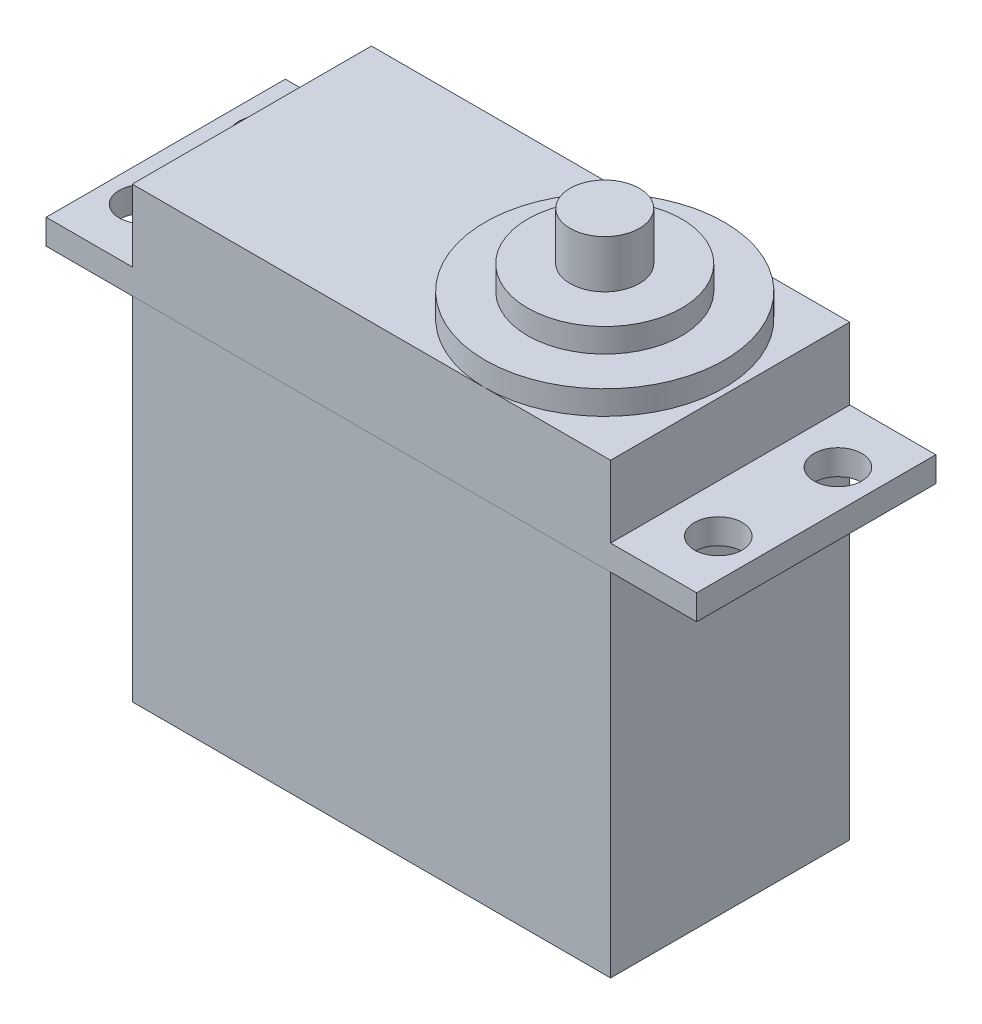
SolidWorks part; units mm, degrees
ref_plane "Alzado" through (0, 0, 0) normal (0, 0, 1) x (1, 0, 0)
ref_plane "Planta" through (0, 0, 0) normal (0, 1, 0) x (1, 0, 0)
ref_plane "Vista lateral" through (0, 0, 0) normal (1, 0, 0) x (0, 0, -1)
sketch "Croquis1" plane through (0, 0, 0) normal (0, 1, 0) x (1, 0, 0)
  line L0 (0, 0) -> (40, 0)
  line L1 (40, 0) -> (40, -20)
  line L2 (0, 0) -> (0, -20)
  line L3 (0, -20) -> (40, -20)
extrude "Saliente-Extruir1" add sketch "Croquis1" along normal blind 29.4
sketch "Croquis2" plane through (0, 29.4, 0) normal (0, 1, 0) x (1, 0, 0)
  line L0 (20, 0) -> (-7.2, 0)
  line L1 (40, 0) -> (0, 0) construction
  line L2 (20, 0) -> (47.2, 0)
  line L3 (-7.2, 0) -> (-7.2, -20.0033)
  line L4 (-7.2, -20.0033) -> (47.2, -20.0033)
  line L5 (47.2, -20.0033) -> (47.2, 0)
extrude "Saliente-Extruir2" add sketch "Croquis2" along normal blind 2.1
sketch "Croquis3" plane through (0, 31.5, 0) normal (0, 1, 0) x (1, 0, 0)
  circle A0 centre (-4.0958, -5.0008) radius 2
  circle A1 centre (-4.0958, -15.0025) radius 2
  circle A2 centre (44.0105, -5.0008) radius 2
  circle A3 centre (44.0105, -15.0025) radius 2
extrude "Cortar-Extruir1" cut sketch "Croquis3" against normal blind 2.1
sketch "Croquis4" plane through (0, 31.5, 0) normal (0, 1, 0) x (1, 0, 0)
  line L2 (0, 0) -> (0, -20.0033)
  line L3 (-7.2, -20.0033) -> (47.2, -20.0033) construction
  line L4 (0, -20.0033) -> (40.0016, -20.0033)
  line L5 (40.0016, -20.0033) -> (40, 0)
  line L6 (40, 0) -> (0, 0)
extrude "Saliente-Extruir3" add sketch "Croquis4" along normal blind 6
sketch "Croquis5" plane through (0, 37.5, 0) normal (0, 1, 0) x (1, 0, 0)
  line L0 (40.0008, -10.0017) -> (29.5104, -10.0017)
  line L1 (40.0016, -20.0033) -> (40, 0) construction
  circle A0 centre (29.5104, -10.0017) radius 10.0017
extrude "Saliente-Extruir4" add sketch "Croquis5" along normal blind 2
sketch "Croquis6" plane through (0, 39.5, 0) normal (0, 1, 0) x (1, 0, 0)
  circle A0 centre (29.5104, -10.0017) radius 6.45
extrude "Saliente-Extruir5" add sketch "Croquis6" along normal blind 2
sketch "Croquis7" plane through (0, 41.5, 0) normal (0, 1, 0) x (1, 0, 0)
  circle A0 centre (29.5104, -10.0017) radius 2.9
extrude "Saliente-Extruir6" add sketch "Croquis7" along normal blind 4
